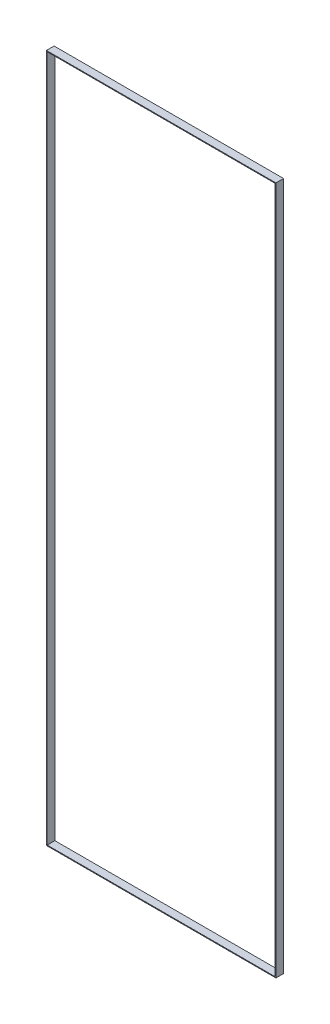
SolidWorks part; units mm, degrees
ref_plane "Front Plane" through (0, 0, 0) normal (0, 0, 1) x (1, 0, 0)
ref_plane "Top Plane" through (0, 0, 0) normal (0, 1, 0) x (1, 0, 0)
ref_plane "Right Plane" through (0, 0, 0) normal (1, 0, 0) x (0, 0, -1)
sketch "Sketch1" plane through (0, 0, 0) normal (0, 0, 1) x (1, 0, 0)
  line L1 (300, -900) -> (-300, -900)
  line L2 (300, -900) -> (300, 900)
  line L3 (300, 900) -> (-300, 900)
  line L4 (-300, -900) -> (-300, 900)
  line L5 (300, -900) -> (-300, 900) construction
  line L6 (300, 900) -> (-300, -900) construction
  line L7 (298, -898) -> (-298, -898)
  line L8 (298, -898) -> (298, 898)
  line L9 (298, 898) -> (-298, 898)
  line L10 (-298, -898) -> (-298, 898)
  line L11 (298, -898) -> (-298, 898) construction
  line L12 (298, 898) -> (-298, -898) construction
  point P0 (0, 0)
  point P6 (0, 0)
  dimension "D1" = 600
  dimension "D2" = 1800
  dimension "D3" = 596
  dimension "D4" = 1796
extrude "Boss-Extrude1" add sketch "Sketch1" along normal blind 20
